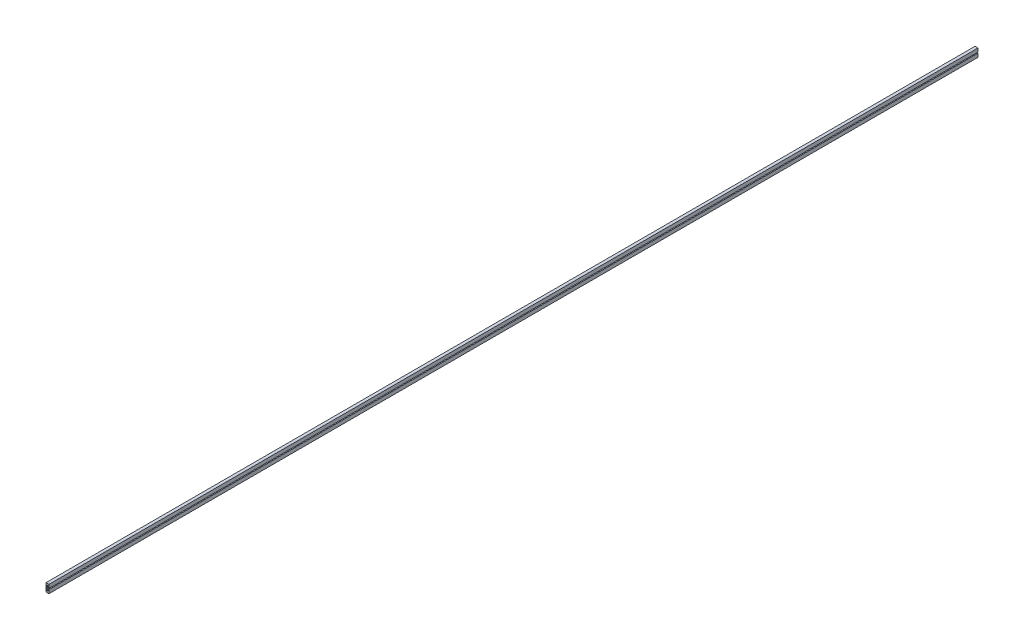
SolidWorks part; units mm, degrees
material "Flexible Plastic"
ref_plane "Front Plane" through (0, 0, 0) normal (0, 0, 1) x (1, 0, 0)
ref_plane "Top Plane" through (0, 0, 0) normal (0, 1, 0) x (1, 0, 0)
ref_plane "Right Plane" through (0, 0, 0) normal (1, 0, 0) x (0, 0, -1)
sketch "Sketch5" plane through (0, 0, 0) normal (0, 0, 1) x (1, 0, 0)
  line L0 (0, 0) -> (3, 0)
  line L1 (3, 0) -> (3, 11)
  line L2 (3, 11) -> (-6, 11)
  line L3 (-6, 11) -> (-6, -14)
  line L4 (-6, -14) -> (3, -14)
  line L5 (3, -14) -> (3, -3)
  line L6 (3, -3) -> (0, -3)
  line L7 (0, -3) -> (0, -9)
  line L8 (0, -9) -> (-3, -9)
  line L9 (-3, -9) -> (-3, 6)
  line L10 (-3, 6) -> (0, 6)
  line L11 (0, 6) -> (0, 0)
  point P14 (-3, -1.5)
  point P15 (-6, -1.5)
  dimension "D1" = 3
  dimension "D2" = 3
  dimension "D3" = 3
  dimension "D4" = 25
  dimension "D5" = 15
  dimension "D6" = 3
extrude "Boss-Extrude1" add sketch "Sketch5" along normal blind 2845
